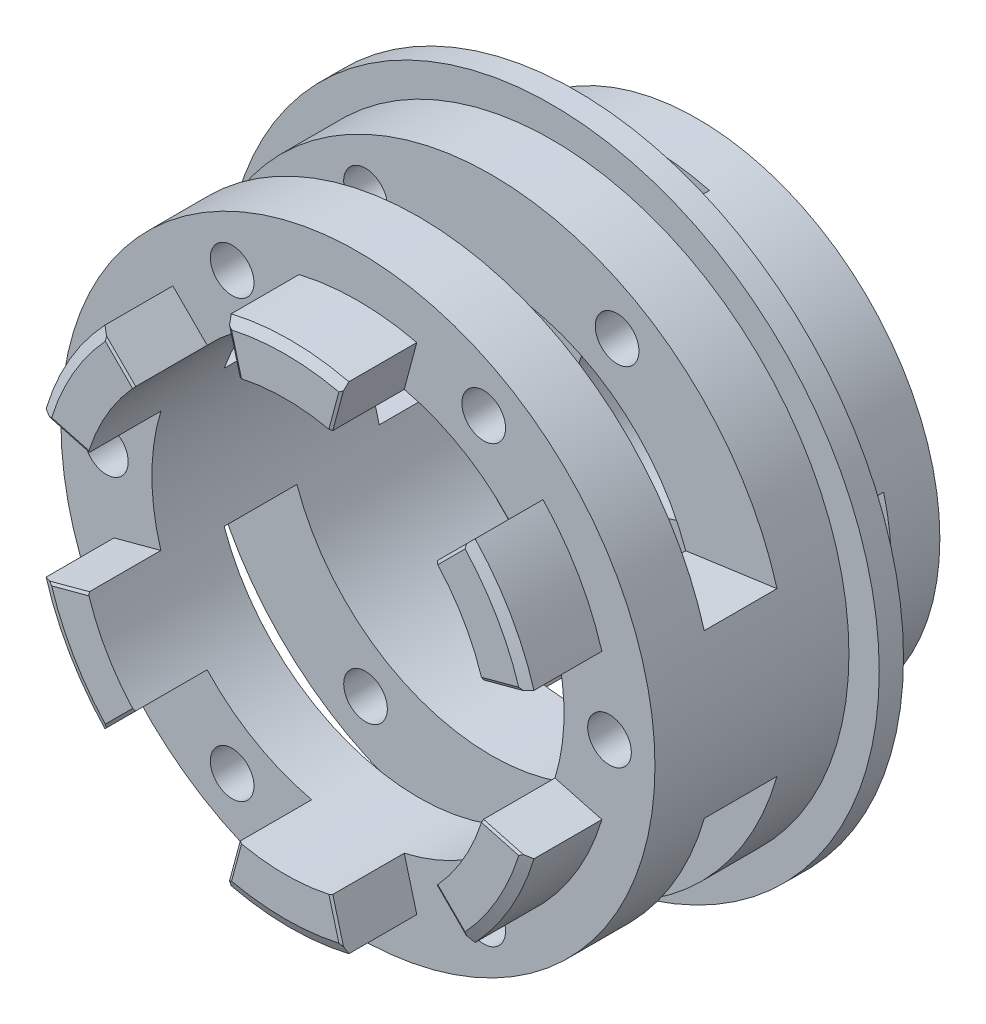
SolidWorks part; units mm, degrees
ref_plane "정면" through (0, 0, 0) normal (0, 0, 1) x (1, 0, 0)
ref_plane "윗면" through (0, 0, 0) normal (0, 1, 0) x (1, 0, 0)
ref_plane "우측면" through (0, 0, 0) normal (1, 0, 0) x (0, 0, -1)
sketch "스케치1" plane through (0, 0, 0) normal (0, 0, 1) x (1, 0, 0)
  circle A0 centre (0, 0) radius 10
  dimension "D1" = 20
extrude "보스-돌출1" add sketch "스케치1" along normal blind 2
sketch "스케치2" plane through (0, 0, 2) normal (0, 0, 1) x (1, 0, 0)
  circle A0 centre (0, 0) radius 10
  circle A1 centre (0, 0) radius 8.5
  circle A5 centre (0, 0) radius 10 construction
  dimension "D1" = 1.5
extrude "보스-돌출2" add sketch "스케치2" along normal blind 3
sketch "스케치4" plane through (0, 0, 5) normal (0, 0, 1) x (1, 0, 0)
  circle A0 centre (0, 0) radius 13.5
  circle A1 centre (0, 0) radius 8.5
  circle A2 centre (0, 0) radius 8.5 construction
  dimension "D1" = 27
extrude "보스-돌출3" add sketch "스케치4" along normal blind 1
sketch "스케치5" plane through (0, 0, 6) normal (0, 0, 1) x (1, 0, 0)
  circle A0 centre (0, 0) radius 8.5
  circle A1 centre (0, 0) radius 12.25
  circle A2 centre (0, 0) radius 8.5 construction
  dimension "D1" = 24.5
extrude "보스-돌출4" add sketch "스케치5" along normal blind 8
sketch "스케치6" plane through (0, 0, 14) normal (0, 0, 1) x (1, 0, 0)
  circle A0 centre (0, 0) radius 10.375 construction
  circle A6 centre (0, 0) radius 8.5 construction
  circle A8 centre (10.375, 0) radius 0.9
  circle A9 centre (5.1875, -8.985) radius 0.9
  circle A10 centre (-5.1875, -8.985) radius 0.9
  circle A11 centre (-10.375, 0) radius 0.9
  circle A12 centre (-5.1875, 8.985) radius 0.9
  circle A13 centre (5.1875, 8.985) radius 0.9
  point P19 (0, 0)
  point P20 (0, 0)
  dimension "D1" = 1.875
  dimension "D2" = 1.8
  dimension "D3" = 6
extrude "컷-돌출1" cut sketch "스케치6" against normal blind 8
sketch "스케치7" plane through (0, 0, 0) normal (0, 0, -1) x (-1, 0, 0)
  circle A0 centre (0, 0) radius 7 construction
  circle A5 centre (0, 0) radius 3
  circle A6 centre (-7, 0) radius 1.15
  circle A7 centre (7, 0) radius 1.15
  circle A9 centre (0, 7) radius 1.15
  circle A11 centre (0, -7) radius 1.15
  dimension "D1" = 14
  dimension "D2" = 2.3
  dimension "D4" = 6
extrude "컷-돌출2" cut sketch "스케치7" against normal through all
sketch "스케치8" plane through (0, 0, 0) normal (0, 1, 0) x (1, 0, 0)
  line L0 (10, 0) -> (-10, 0) construction
  line L1 (-2.5, -2) -> (2.5, -2)
  line L2 (-2.5, -2) -> (-2.5, -5)
  line L3 (-2.5, -5) -> (2.5, -5)
  line L4 (2.5, -2) -> (2.5, -5)
  line L5 (-2.5, -2) -> (2.5, -5) construction
  line L6 (-2.5, -5) -> (2.5, -2) construction
  line L8 (10, -5) -> (10, 0) construction
  line L9 (-10, 0) -> (-10, -5) construction
  line L10 (10, -5) -> (-10, -5) construction
  point P0 (0, -3.5)
  dimension "D1" = 2
  dimension "D3" = 7.5
  dimension "D4" = 7.5
extrude "컷-돌출3" cut sketch "스케치8" against normal through all both and the other way through all
sketch "스케치9" plane through (0, 0, 0) normal (1, 0, 0) x (0, 0, -1)
  line L0 (-5, -9.6825) -> (-5, 9.6825) construction
  line L1 (-5, -2.5) -> (-2, -2.5)
  line L2 (-5, -2.5) -> (-5, 2.5)
  line L3 (-5, 2.5) -> (-2, 2.5)
  line L4 (-2, -2.5) -> (-2, 2.5)
  line L5 (0, 10) -> (-2, 10) construction
  line L6 (-2, -10) -> (0, -10) construction
  line L7 (0, -10) -> (0, 10) construction
  dimension "D1" = 7.5
  dimension "D2" = 7.5
  dimension "D3" = 2
extrude "컷-돌출4" cut sketch "스케치9" against normal through all both and the other way through all
sketch "스케치10" plane through (0, 0, 14) normal (0, 0, 1) x (1, 0, 0)
  line L1 (2.2, 8.2104) -> (2.7176, 10.1422)
  line L3 (6.0104, 6.0104) -> (7.4246, 7.4246)
  line L5 (8.2104, 2.2) -> (10.1422, 2.7176)
  line L7 (8.2104, -2.2) -> (10.1422, -2.7176)
  line L9 (6.0104, -6.0104) -> (7.4246, -7.4246)
  line L11 (2.2, -8.2104) -> (2.7176, -10.1422)
  line L13 (-2.2, -8.2104) -> (-2.7176, -10.1422)
  line L15 (-6.0104, -6.0104) -> (-7.4246, -7.4246)
  line L17 (-8.2104, -2.2) -> (-10.1422, -2.7176)
  line L19 (-8.2104, 2.2) -> (-10.1422, 2.7176)
  line L21 (-6.0104, 6.0104) -> (-7.4246, 7.4246)
  line L23 (-2.2, 8.2104) -> (-2.7176, 10.1422)
  arc A0 (-7.4246, 7.4246) -> (-10.1422, 2.7176) centre (0, 0) ccw
  arc A1 (-8.2104, -2.2) -> (-6.0104, -6.0104) centre (0, 0) ccw
  arc A2 (2.7176, 10.1422) -> (-2.7176, 10.1422) centre (0, 0) ccw
  arc A3 (10.1422, 2.7176) -> (7.4246, 7.4246) centre (0, 0) ccw
  arc A4 (7.4246, -7.4246) -> (10.1422, -2.7176) centre (0, 0) ccw
  arc A5 (-2.7176, -10.1422) -> (2.7176, -10.1422) centre (0, 0) ccw
  arc A6 (-10.1422, -2.7176) -> (-7.4246, -7.4246) centre (0, 0) ccw
  arc A7 (-2.2, -8.2104) -> (2.2, -8.2104) centre (0, 0) ccw
  arc A8 (6.0104, -6.0104) -> (8.2104, -2.2) centre (0, 0) ccw
  arc A9 (8.2104, 2.2) -> (6.0104, 6.0104) centre (0, 0) ccw
  arc A10 (2.2, 8.2104) -> (-2.2, 8.2104) centre (0, 0) ccw
  arc A11 (-6.0104, 6.0104) -> (-8.2104, 2.2) centre (0, 0) ccw
  circle A12 centre (0, 0) radius 8.5 construction
  arc A13 (8.124, 2.5) -> (2.5, 8.124) centre (0, 0) ccw construction
  point P30 (0, 0)
  dimension "D1" = 2
extrude "보스-돌출5" add sketch "스케치10" along normal blind 3
chamfer "모따기1" distance 0.2 angle 64 18 edges at (-9.1763, -2.4588, 17) (-6.7175, -6.7175, 17) (-2.4588, -9.1763, 17) (2.4588, -9.1763, 17) (6.7175, -6.7175, 17) (9.1763, -2.4588, 17) (9.1763, 2.4588, 17) (6.7175, 6.7175, 17) (2.4588, 9.1763, 17) (-2.4588, 9.1763, 17) (-6.7175, 6.7175, 17) (-9.1763, 2.4588, 17) (-9.0933, -5.25, 17) (0, -10.5, 17) (9.0933, -5.25, 17) (9.0933, 5.25, 17) (0, 10.5, 17) (-9.0933, 5.25, 17)
sketch "Sketch1" plane through (0, 0, 14) normal (0, 0, 1) x (1, 0, 0)
  line L12 (-1.8105, 7.9158) -> (-5.4816, 5.0574)
  line L13 (-8.0247, 2.4608) -> (-7.6348, -2.3563)
  line L14 (-5.9001, -5.4758) -> (-1.7847, -7.8199)
  line L15 (1.8447, -8.0436) -> (5.6417, -5.2174)
  line L16 (7.4387, -2.3038) -> (7.6354, 2.3565)
  line L17 (5.9887, 5.5644) -> (1.8127, 7.9244)
  line L18 (-2.5214, 10.5692) -> (-8.347, 7.9227)
  line L19 (-10.5347, 3.1333) -> (-10.6301, -3.1589)
  line L20 (-7.9043, -7.48) -> (-2.5564, -10.6996)
  line L21 (7.9597, -7.5355) -> (2.5565, -10.6999)
  line L22 (10.5949, -3.1495) -> (10.4674, 3.1153)
  line L23 (7.9322, 7.508) -> (2.5288, 10.5967)
  line L24 (-8.347, 7.9227) -> (-5.4816, 5.0574)
  line L25 (-8.0247, 2.4608) -> (-10.5347, 3.1333)
  line L26 (-10.6301, -3.1589) -> (-7.6348, -2.3563)
  line L27 (-5.9001, -5.4758) -> (-7.9043, -7.48)
  line L28 (-2.5564, -10.6996) -> (-1.7847, -7.8199)
  line L29 (1.8447, -8.0436) -> (2.5565, -10.6999)
  line L30 (7.9597, -7.5355) -> (5.6417, -5.2174)
  line L31 (7.4387, -2.3038) -> (10.5949, -3.1495)
  line L32 (10.4674, 3.1153) -> (7.6354, 2.3565)
  line L33 (5.9887, 5.5644) -> (7.9322, 7.508)
  line L34 (2.5288, 10.5967) -> (1.8127, 7.9244)
  line L35 (-1.8105, 7.9158) -> (-2.5214, 10.5692)
extrude "Cut-Extrude1" cut sketch "Sketch1" along normal blind 28
ref_plane "Plane1" through (0, 0, 10) normal (0, 0, 1) x (1, 0, 0)
sketch "Sketch2" plane through (0, 0, 10) normal (0, 0, 1) x (1, 0, 0)
  line L0 (0, 1.6981) -> (-22.4726, 4.8531)
  line L1 (0, -9.35) -> (0, 9.35) construction
  line L2 (-22.4726, 4.8531) -> (-22.4726, 17.0393)
  line L3 (-22.4726, 17.0393) -> (22.4726, 17.0393)
  line L4 (0, 1.6981) -> (22.4726, 4.8531)
  line L5 (22.4726, 4.8531) -> (22.4726, 17.0393)
  line L6 (9.35, 0) -> (-9.35, 0) construction
  line L7 (0, -1.6981) -> (-22.4726, -4.8531)
  line L8 (-22.4726, -4.8531) -> (-22.4726, -17.0393)
  line L9 (-22.4726, -17.0393) -> (22.4726, -17.0393)
  line L10 (22.4726, -4.8531) -> (22.4726, -17.0393)
  line L11 (0, -1.6981) -> (22.4726, -4.8531)
  point P8 (0, 17.0393)
extrude "Cut-Extrude2" cut sketch "Sketch2" against normal blind 1.5 and the other way blind 1.5
